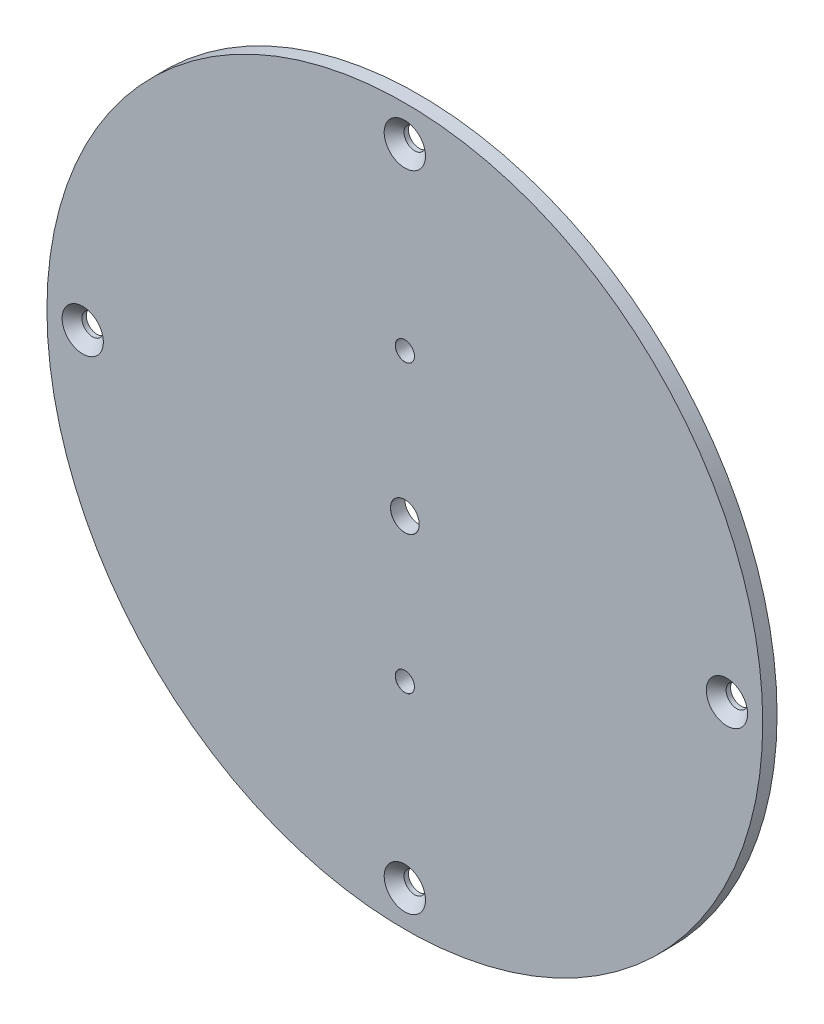
SolidWorks part; units mm, degrees
ref_plane "Płaszczyzna przednia" through (0, 0, 0) normal (0, 0, 1) x (1, 0, 0)
ref_plane "Płaszczyzna górna" through (0, 0, 0) normal (0, 1, 0) x (1, 0, 0)
ref_plane "Płaszczyzna prawa" through (0, 0, 0) normal (1, 0, 0) x (0, 0, -1)
sketch "Szkic1" plane through (0, 0, 0) normal (0, 0, 1) x (1, 0, 0)
  circle A0 centre (0, 0) radius 150
  dimension "D1" = 300
extrude "Dodanie-wyciągnięcie1" add sketch "Szkic1" along normal blind 6
sketch "Szkic2" plane through (0, 0, 6) normal (0, 0, 1) x (1, 0, 0)
  line L0 (0, 0) -> (105.8893, 0) construction
  line L1 (0, 0) -> (0, 82.1396) construction
  point P1 (0, 60)
  point P3 (0, 0)
  point P6 (0, -60)
  dimension "D2" = 60
hole_wizard "Otwory ustalające Ø8.0mm1" positions "Szkic3" profile "Szkic4" hole size "Ø8.0" standard "Ansi Metric" end condition through all
sketch "Szkic3" plane through (0, 0, 6) normal (0, 0, 1) x (1, 0, 0)
  point P0 (0, 60)
  point P3 (0, -60)
sketch "Szkic4" plane through (0, 60, 6) normal (1, 0, 0) x (0, -1, 0)
  line L0 (0, 0) -> (0, 6)
  line L1 (0, 6) -> (4, 6)
  line L2 (4, 6) -> (4, 0.025)
  line L3 (4, 0.025) -> (4.025, 0)
  line L5 (4.025, 0) -> (0, 0)
  line L6 (-4, 0.025) -> (-4.025, 0) construction
  line L11 (0, -6.35) -> (0, 107.95) construction
  dimension "Średnica otworu na wylot" = 8
  dimension "Głębokość otworu na wylot" = 6
  dimension "Średnica zewnętrznego pogłębienia stożkowego" = 8.05
  dimension "Kąt zewnętrznego pogłębienia stożkowego" = 90
hole_wizard "Otwory ustalające Ø12.0mm1" positions "Szkic5" profile "Szkic6" hole size "Ø12.0" standard "Ansi Metric" end condition through all
sketch "Szkic5" plane through (0, 0, 6) normal (0, 0, 1) x (1, 0, 0)
  point P0 (0, 0)
sketch "Szkic6" plane through (0, 0, 6) normal (1, 0, 0) x (0, -1, 0)
  line L0 (0, 0) -> (0, 6)
  line L1 (0, 6) -> (6, 6)
  line L2 (6, 6) -> (6, 0.025)
  line L3 (6, 0.025) -> (6.025, 0)
  line L5 (6.025, 0) -> (0, 0)
  line L6 (-6, 0.025) -> (-6.025, 0) construction
  line L11 (0, -6.35) -> (0, 107.95) construction
  dimension "Średnica otworu na wylot" = 12
  dimension "Głębokość otworu na wylot" = 6
  dimension "Średnica zewnętrznego pogłębienia stożkowego" = 12.05
  dimension "Kąt zewnętrznego pogłębienia stożkowego" = 90
sketch "Szkic7" plane through (0, 0, 6) normal (0, 0, 1) x (1, 0, 0)
  point P0 (0, 135)
  point P5 (135, 0)
  point P6 (0, -135)
  point P7 (-135, 0)
  point P8 (0, 0)
  dimension "D1" = 135
  dimension "D2" = 4
hole_wizard "Pogłębienie stożkowe pod M8 wkręt do części metalowych z łbem soczewkowym1" positions "Szkic8" profile "Szkic10" countersink size "M8" standard "Ansi Metric" end condition through all
sketch "Szkic8" plane through (0, 0, 6) normal (0, 0, 1) x (1, 0, 0)
  point P0 (0, 135)
  point P3 (135, 0)
  point P6 (0, -135)
  point P9 (-135, 0)
sketch "Szkic10" plane through (0, 135, 6) normal (1, 0, 0) x (0, -1, 0)
  line L0 (0, 0) -> (0, 6)
  line L1 (0, 6) -> (4.5, 6)
  line L2 (4.5, 6) -> (4.5, 4.15)
  line L3 (4.5, 4.15) -> (8.65, 0)
  line L5 (8.65, 0) -> (0, 0)
  line L6 (-4.5, 4.15) -> (-8.65, 0) construction
  line L11 (0, -6.35) -> (0, 107.95) construction
  dimension "Średnica otworu na wylot" = 9
  dimension "Głębokość otworu na wylot" = 6
  dimension "Średnica zewnętrznego pogłębienia stożkowego" = 17.3
  dimension "Kąt zewnętrznego pogłębienia stożkowego" = 90
